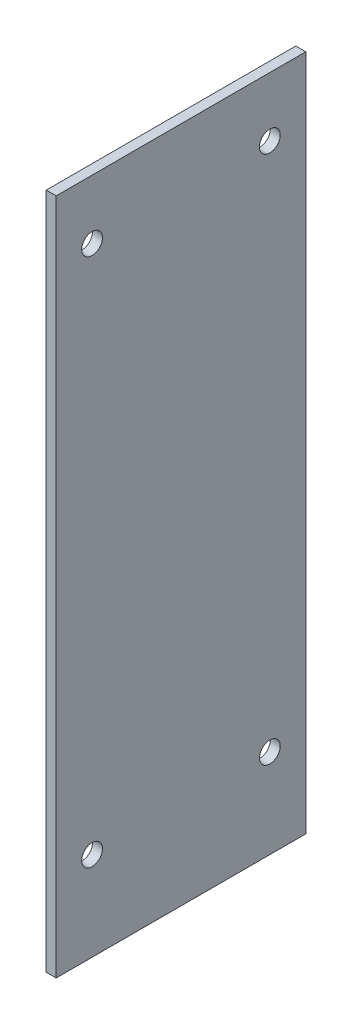
SolidWorks part; units mm, degrees
ref_plane "Front Plane" through (0, 0, 0) normal (0, 0, 1) x (1, 0, 0)
ref_plane "Top Plane" through (0, 0, 0) normal (0, 1, 0) x (1, 0, 0)
ref_plane "Right Plane" through (0, 0, 0) normal (1, 0, 0) x (0, 0, -1)
sketch "Sketch1" plane through (0, 0, 0) normal (1, 0, 0) x (0, 0, -1)
  line L0 (55, 0) -> (-55, 0) construction
  line L1 (-21.06, 0) -> (21.06, 0)
  line L2 (-21.06, 0) -> (-21.06, 114.3)
  line L3 (-21.06, 114.3) -> (21.06, 114.3)
  line L4 (21.06, 0) -> (21.06, 114.3)
  point P6 (0, 0)
  dimension "D1" = 42.12
  dimension "D2" = 114.3
extrude "Boss-Extrude1" add sketch "Sketch1" along normal blind 1.68
sketch "Sketch2" plane through (1.68, 0, 0) normal (1, 0, 0) x (0, 0, -1)
  line L0 (21.06, 114.3) -> (-21.06, 114.3) construction
  line L1 (0.924, 0) -> (-0.924, 0) construction
  line L4 (-15, 104.3) -> (15, 104.3) construction
  line L5 (0, 0.924) -> (0, -0.924) construction
  circle A0 centre (-15, 104.3) radius 1.75
  circle A1 centre (15, 104.3) radius 1.75
  circle A2 centre (15, 15) radius 1.75
  circle A3 centre (-15, 15) radius 1.75
  point P12 (-7.439, 104.3)
  point P13 (0, 104.3)
  dimension "D1" = 3.5
  dimension "D2" = 10
  dimension "D3" = 15
  dimension "D4" = 30
extrude "Cut-Extrude1" cut sketch "Sketch2" against normal through all
